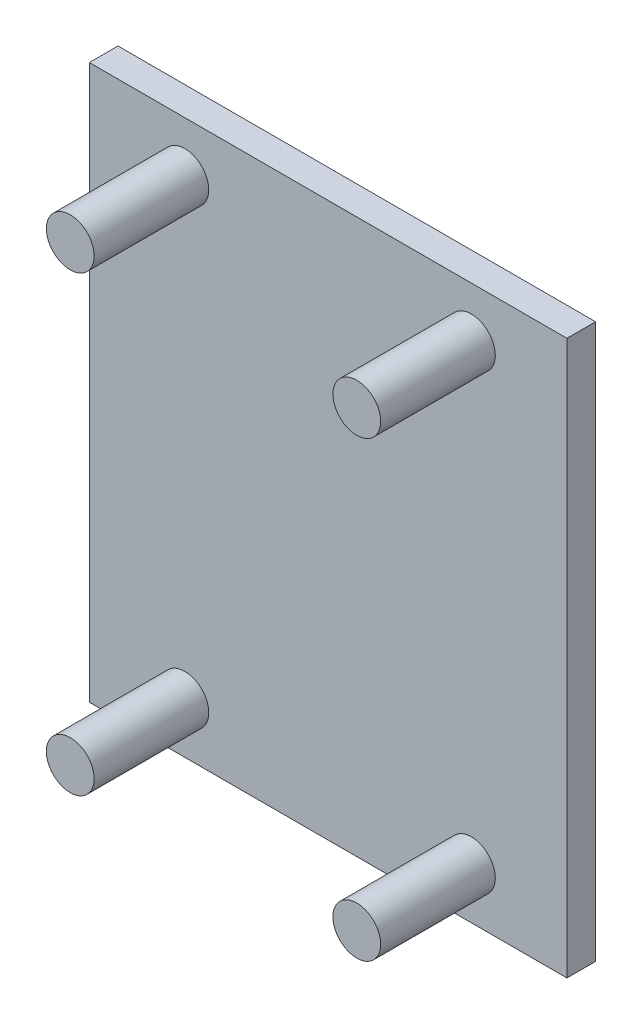
SolidWorks part; units mm, degrees
ref_plane "Спереди" through (0, 0, 0) normal (0, 0, 1) x (1, 0, 0)
ref_plane "Сверху" through (0, 0, 0) normal (0, 1, 0) x (1, 0, 0)
ref_plane "Справа" through (0, 0, 0) normal (1, 0, 0) x (0, 0, -1)
sketch "Эскиз1" plane through (0, 0, 0) normal (0, 0, 1) x (1, 0, 0)
  line L0 (-25, -29) -> (25, -29)
  line L1 (25, -29) -> (25, 29)
  line L2 (25, 29) -> (-25, 29)
  line L3 (-25, 29) -> (-25, -29)
extrude "Former_base" add sketch "Эскиз1" along normal blind 3
sketch "Эскиз2" plane through (0, 0, 0) normal (0, 0, 1) x (1, 0, 0)
  circle A0 centre (-15, -23.7) radius 2.5
  circle A1 centre (-15, 23.7) radius 2.5
  circle A2 centre (15, -23.7) radius 2.5
  circle A3 centre (15, 23.7) radius 2.5
extrude "Former_posts" add sketch "Эскиз2" along normal blind 12 from offset 3
